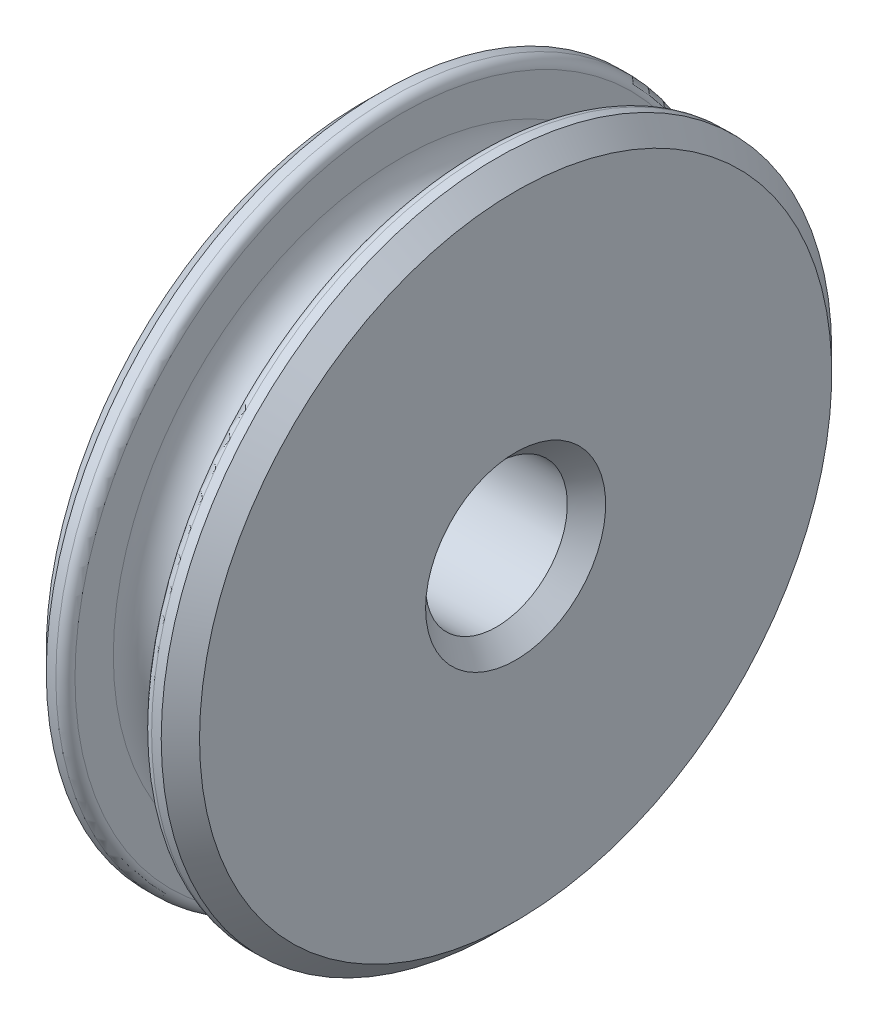
SolidWorks part; units mm, degrees
material "Nylon 101"
ref_plane "Front" through (0, 0, 0) normal (0, 0, 1) x (1, 0, 0)
ref_plane "Top" through (0, 0, 0) normal (0, 1, 0) x (1, 0, 0)
ref_plane "Right" through (0, 0, 0) normal (1, 0, 0) x (0, 0, -1)
sketch "Sketch1" plane through (0, 0, 0) normal (0, 0, 1) x (1, 0, 0)
  line L0 (0, 0) -> (2.2033, 0) construction
  line L1 (0, 8.75) -> (0, 1.85)
  line L2 (0, 1.85) -> (4, 1.85)
  line L3 (4, 1.85) -> (4, 8.75)
  line L4 (4, 8.75) -> (3, 8.75)
  line L5 (3, 8.75) -> (3, 7.5)
  line L7 (1, 7.5) -> (1, 8.75)
  line L8 (1, 8.75) -> (0, 8.75)
  arc A2 (1, 7.5) -> (3, 7.5) centre (2, 7.5) ccw
  dimension "D1" = 3.7
  dimension "D4" = 15
  dimension "D2" = 1
  dimension "D3" = 4
  dimension "D5" = 17.5
revolve "Revolve1" add sketch "Sketch1" angle 360 about L0
fillet "Fillet1" radius 0.25 2 edges at (3, 0, 8.75) (1, 0, 8.75)
chamfer "Chamfer1" distance 0.5 angle 45 4 edges at (4, 0, 1.85) (4, 0, 8.75) (0, 0, 8.75) (0, 0, 1.85)
